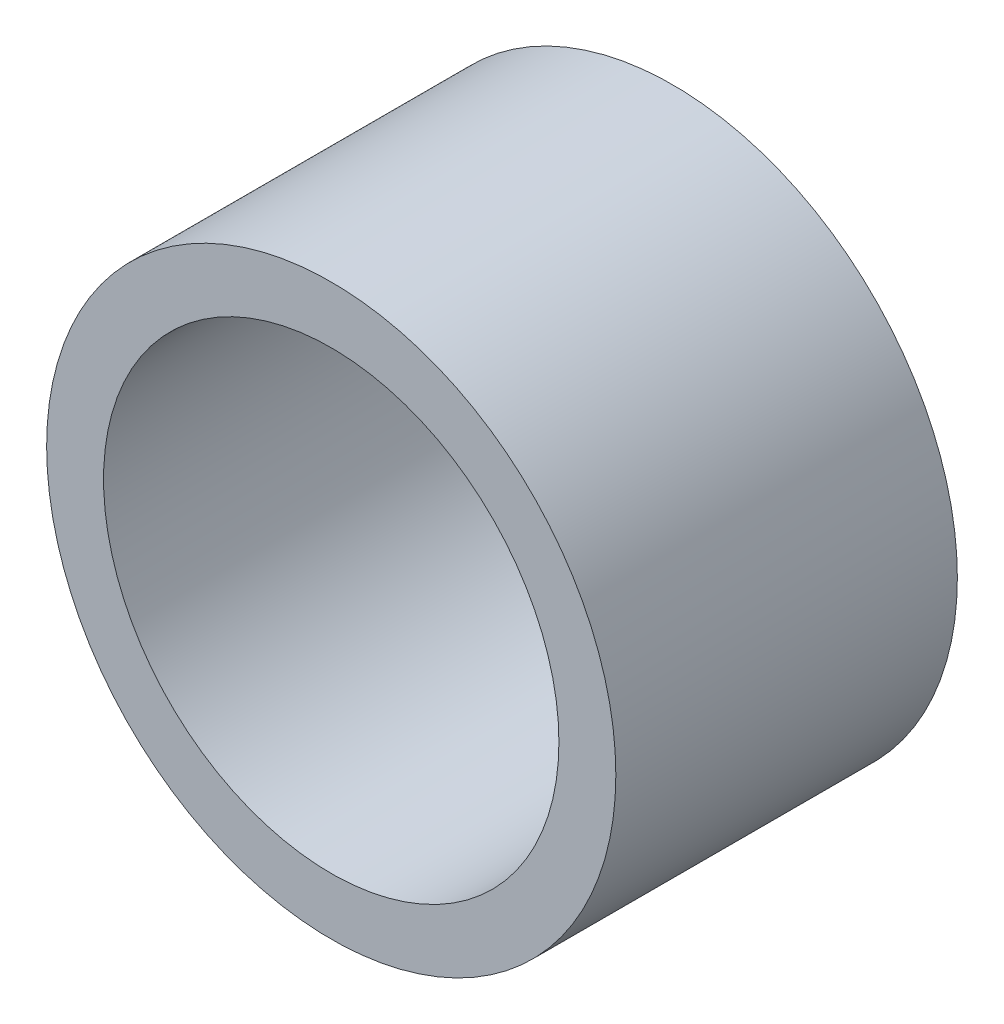
SolidWorks part; units mm, degrees
ref_plane "Front Plane" through (0, 0, 0) normal (0, 0, 1) x (1, 0, 0)
ref_plane "Top Plane" through (0, 0, 0) normal (0, 1, 0) x (1, 0, 0)
ref_plane "Right Plane" through (0, 0, 0) normal (1, 0, 0) x (0, 0, -1)
sketch "Sketch1" plane through (0, 0, 0) normal (0, 0, 1) x (1, 0, 0)
  circle A0 centre (0, 0) radius 8
  circle A1 centre (0, 0) radius 10
  dimension "D1" = 16
  dimension "12" = 20
extrude "Boss-Extrude1" add sketch "Sketch1" along normal blind 12
